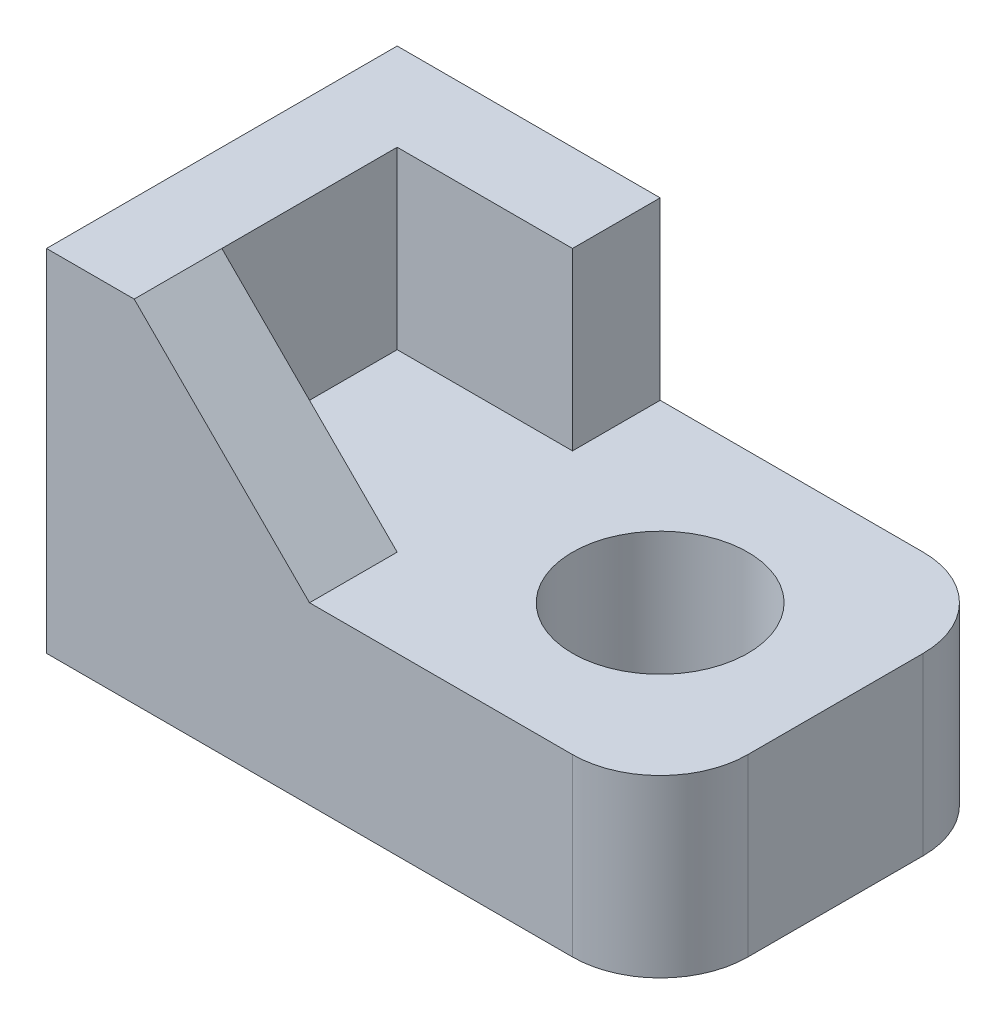
SolidWorks part; units mm, degrees
ref_plane "前基準面" through (0, 0, 0) normal (0, 0, 1) x (1, 0, 0)
ref_plane "上基準面" through (0, 0, 0) normal (0, 1, 0) x (1, 0, 0)
ref_plane "右基準面" through (0, 0, 0) normal (1, 0, 0) x (0, 0, -1)
sketch "草圖1" plane through (0, 0, 0) normal (0, 1, 0) x (1, 0, 0)
  line L1 (0, 0) -> (60, 0)
  line L2 (0, 0) -> (0, 40)
  line L3 (0, 40) -> (60, 40)
  line L4 (70, 10) -> (70, 30)
  circle A0 centre (50, 20) radius 10
  arc A1 (70, 30) -> (60, 40) centre (60, 30) ccw
  arc A2 (70, 10) -> (60, 0) centre (60, 10) cw
  point P9 (48.8754, 21.5198)
  point P10 (70, 40)
  point P13 (70, 0)
  dimension "D3" = 20
  dimension "D6" = 10
  dimension "D7" = 10
  dimension "D1" = 40
  dimension "D2" = 70
  dimension "D4" = 20
  dimension "D5" = 20
extrude "填料-伸長1" add sketch "草圖1" along normal blind 20
sketch "草圖2" plane through (0, 20, 0) normal (0, 1, 0) x (1, 0, 0)
  line L0 (0, 0) -> (0, 40)
  line L1 (0, 40) -> (30, 40)
  line L2 (60, 40) -> (0, 40) construction
  line L3 (30, 40) -> (30, 30)
  line L4 (30, 30) -> (10, 30)
  line L5 (10, 30) -> (10, 0)
  line L6 (0, 0) -> (60, 0) construction
  line L7 (10, 0) -> (0, 0)
  dimension "D1" = 10
  dimension "D2" = 10
  dimension "D3" = 30
extrude "填料-伸長2" add sketch "草圖2" along normal blind 20
sketch "草圖3" plane through (0, 0, 0) normal (0, 0, 1) x (1, 0, 0)
  line L0 (10, 40) -> (30, 20)
  line L1 (30, 20) -> (10, 20)
  line L2 (10, 20) -> (30, 20) construction
  line L3 (10, 40) -> (10, 20) construction
  line L4 (10, 20) -> (10, 40)
extrude "填料-伸長3" add sketch "草圖3" against normal blind 10
